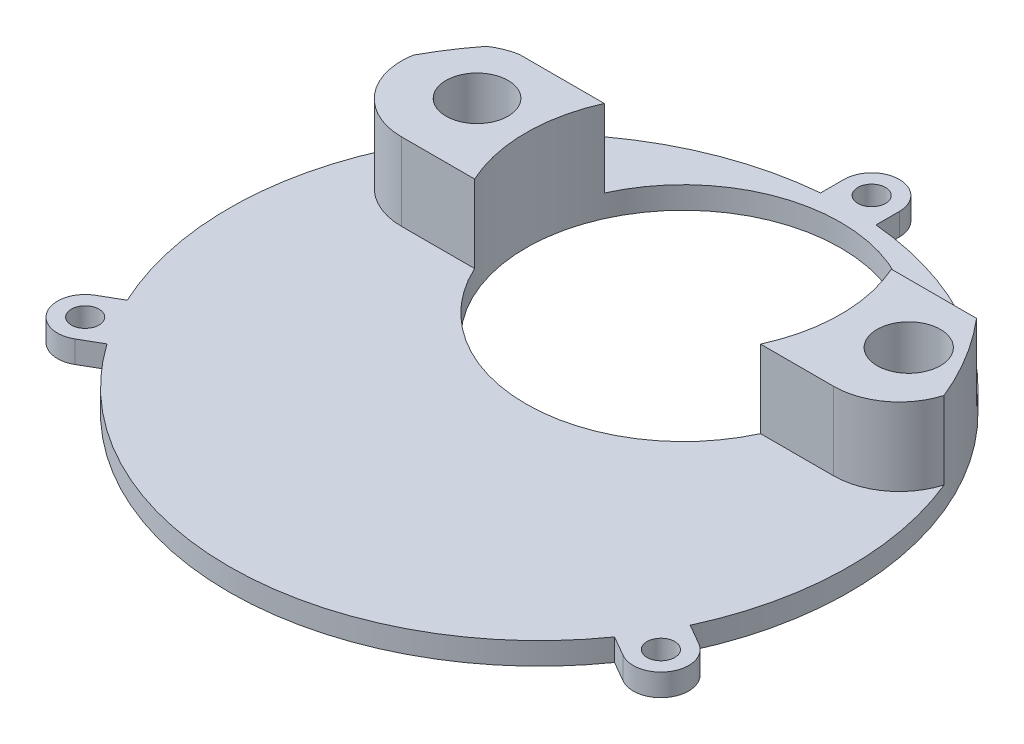
SolidWorks part; units mm, degrees
ref_plane "Front Plane" through (0, 0, 0) normal (0, 0, 1) x (1, 0, 0)
ref_plane "Top Plane" through (0, 0, 0) normal (0, 1, 0) x (1, 0, 0)
ref_plane "Right Plane" through (0, 0, 0) normal (1, 0, 0) x (0, 0, -1)
ref_plane "Plane2" through (0, 2, 0) normal (0, 1, 0) x (1, 0, 0)
sketch "Sketch14" plane through (0, 2, 0) normal (0, 1, 0) x (1, 0, 0)
  line L0 (-25.4019, -11.779) -> (-27.2308, -12.8349)
  line L1 (-24.7308, -17.1651) -> (-22.9019, -16.1091)
  line L2 (22.9019, -16.1091) -> (24.7308, -17.1651)
  line L3 (27.2308, -12.8349) -> (25.4019, -11.779)
  line L4 (2.5, 27.8882) -> (2.5, 30)
  line L5 (-2.5, 30) -> (-2.5, 27.8882)
  arc A0 (-2.5, 27.8882) -> (-25.4019, -11.779) centre (0, 0) ccw
  arc A1 (-27.2308, -12.8349) -> (-24.7308, -17.1651) centre (-25.9808, -15) ccw
  arc A2 (-22.9019, -16.1091) -> (22.9019, -16.1091) centre (0, 0) ccw
  arc A3 (24.7308, -17.1651) -> (27.2308, -12.8349) centre (25.9808, -15) ccw
  arc A4 (25.4019, -11.779) -> (2.5, 27.8882) centre (0, 0) ccw
  arc A5 (2.5, 30) -> (-2.5, 30) centre (0, 30) ccw
extrude "Boss-Extrude3" add sketch "Sketch14" against normal blind 2 separate body
sketch "Sketch15" plane through (0, 2, 0) normal (0, 1, 0) x (-1, 0, 0)
  line L0 (-20.2, -6.3651) -> (18.8, -6.3651)
  line L1 (19.9431, -18.1238) -> (-21.3431, -18.1238)
  arc A0 (-21.3431, -18.1238) -> (-25.8987, -10.6422) centre (0, 0) cw
  arc A1 (-25.8987, -10.6422) -> (-20.2, -6.3651) centre (-20.2, -12.3) cw
  arc A2 (18.8, -6.3651) -> (24.6548, -13.2718) centre (18.8, -12.3) cw
  arc A3 (24.6548, -13.2718) -> (22.0353, -17.2755) centre (0, 0) cw
  arc A4 (22.0353, -17.2755) -> (19.9431, -18.1238) centre (18.8, -12.3) cw
extrude "Boss-Extrude4" add sketch "Sketch15" along normal blind 7
hole_wizard "Ø2.5 (2.5) Diameter Hole2" positions "Sketch21" profile "Sketch20" hole size "Ø2.5" standard "ANSI Metric"
sketch "Sketch21" plane through (0, 2, 0) normal (0, 1, 0) x (1, 0, 0)
  point P0 (-25.9808, -15)
  point P1 (25.9808, -15)
  point P2 (0, 30)
sketch "Sketch20" plane through (-25.9808, 2, 15) normal (1, 0, 0) x (0, 0, 1)
  line L0 (0, 0) -> (0, 2)
  line L1 (0, 2) -> (1.25, 2)
  line L2 (1.25, 2) -> (1.25, 0)
  line L5 (1.25, 0) -> (0, 0)
  line L11 (0, -6.35) -> (0, 107.95) construction
  dimension "Thru Hole Dia." = 2.5
  dimension "Thru Hole Depth" = 2
hole_wizard "M25 Clearance Hole2" positions "Sketch23" profile "Sketch22" hole size "M25" standard "ANSI Metric"
sketch "Sketch23" plane through (0, 0, 0) normal (0, -1, 0) x (-1, 0, 0)
  point P0 (-0.7, 12.3)
sketch "Sketch22" plane through (0.7, 0, -12.3) normal (1, 0, 0) x (0, 0, -1)
  line L0 (0, 0) -> (0, 9)
  line L1 (0, 9) -> (14.2, 9)
  line L2 (14.2, 9) -> (14.2, 0)
  line L5 (14.2, 0) -> (0, 0)
  line L11 (0, -6.35) -> (0, 107.95) construction
  dimension "Thru Hole Dia." = 28.4
  dimension "Thru Hole Depth" = 9
sketch "Sketch27" plane through (0, 9, 0) normal (0, 1, 0) x (1, 0, 0)
  circle A0 centre (-18.3982, 12.7829) radius 2.8
  circle A1 centre (20.5622, 12.7829) radius 2.85
  point P4 (0, 0)
extrude "Cut-Extrude7" cut sketch "Sketch27" against normal blind 5.5
